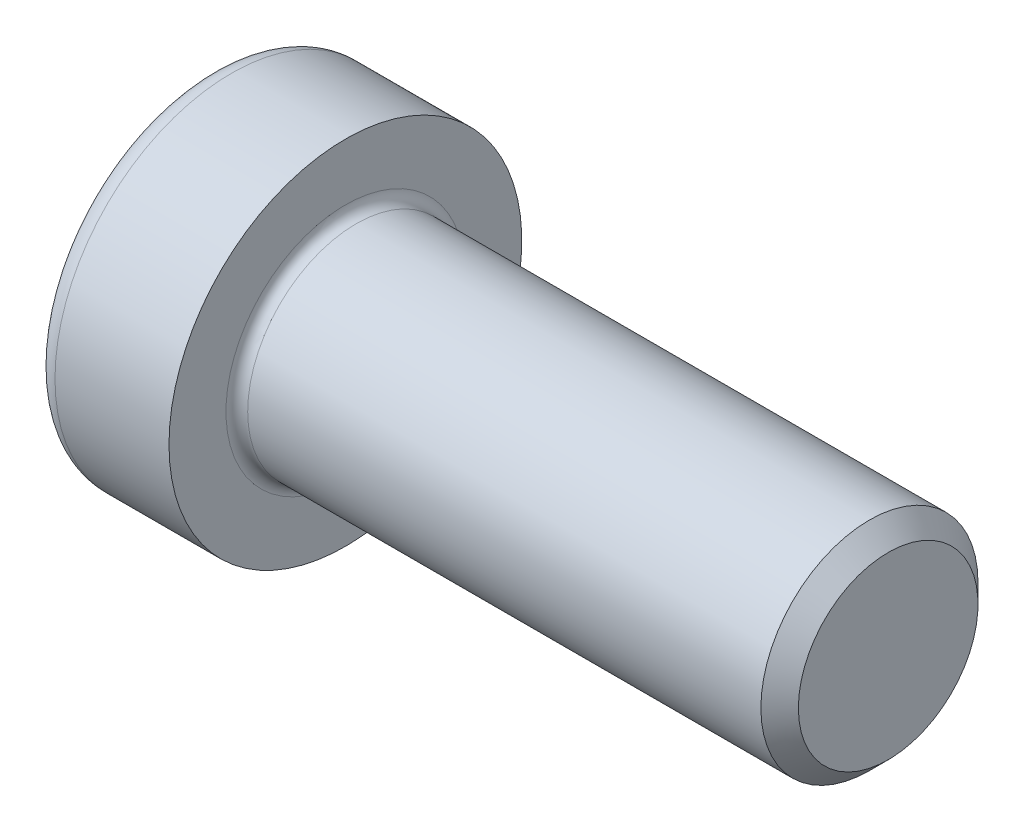
SolidWorks part; units mm, degrees
revolve "Base-Revolve" add sketch "BodySke"
sketch "BodySke" plane through (0, 0, 0) normal (0, 0, 1) x (1, 0, 0)
  line L0 (0, 0) -> (0, 6.5)
  line L1 (0, 6.5) -> (5, 6.5)
  line L2 (5, 6.5) -> (5, 4)
  line L3 (5, 4) -> (24.3095, 4)
  line L4 (25, 3.3095) -> (25, 0)
  line L5 (25, 0) -> (0, 0)
  line L6 (-31.75, 0) -> (127, 0) construction
  line L8 (25, 3.3095) -> (24.3095, 4)
  line L10 (25, -3.3095) -> (24.3095, -4) construction
  line L11 (6.25, 4.525) -> (6.25, -1.825) construction
  line L12 (8.75, 4.525) -> (8.75, -1.825) construction
  line L13 (-35, 4.525) -> (-35, -1.825) construction
  dimension "Head_ht" = 5
  dimension "Length" = 20
  dimension "Body_ch_ang" = 45
  dimension "Diameter" = 8
  dimension "Minor_dia" = 6.619
  dimension "Advance" = 1.25
  dimension "Thread_nom" = 16.25
  dimension "Thread_length" = 60
  dimension "Head_dia" = 13
cosmetic thread "ThreadCosmetic"
fillet "Fillet1" radius 0.4 1 edges at (5, 0, 4)
fillet "Fillet2" radius 0.8 1 edges at (0, 0, 6.5)
material "AISI 316 Нержавеющая сталь, лист (SS)"
ref_plane "Plane1" through (0, 0, 0) normal (0, 0, 1) x (1, 0, 0)
ref_plane "Plane2" through (0, 0, 0) normal (0, 1, 0) x (1, 0, 0)
ref_plane "Plane3" through (0, 0, 0) normal (1, 0, 0) x (0, 0, -1)
other "Configuration Table"
sketch "Sketch2" plane through (0, 0, 0) normal (0, 0, 1) x (1, 0, 0)
  line L0 (0, 2.5) -> (3.8, 2.5)
  line L1 (3.8, 2.5) -> (5.2434, 0)
  line L2 (-31.75, 0) -> (127, 0) construction
  line L3 (5.2434, 0) -> (0, 0)
  line L4 (0, 0) -> (0, 2.5)
  line L6 (0, 0) -> (47.625, 0) construction
  dimension "D1" = 2.5
  dimension "D2" = 60
  dimension "Depth" = 3.8
revolve "Hex-PreBroach" cut sketch "Sketch2" angle 360 about L6
sketch "Sketch3" plane through (0, 0, 0) normal (-1, 0, 0) x (0, 0.5, 0.866)
  line L0 (1.4434, 2.5) -> (-1.4434, 2.5)
  line L1 (-1.4434, 2.5) -> (-2.8868, 0)
  line L2 (1.4434, 2.5) -> (2.8868, 0)
  line L3 (1.4434, -2.5) -> (2.8868, 0)
  line L4 (1.4434, -2.5) -> (-1.4434, -2.5)
  line L5 (-1.4434, -2.5) -> (-2.8868, 0)
  dimension "D1" = 2.5
  dimension "D2" = 2.5
  dimension "Hex_size" = 5
extrude "Hex" cut sketch "Sketch3" against normal blind 3.8
sketch "ThdSchSke" plane through (0, 0, 0) normal (0, 0, 1) x (1, 0, 0)
  line L0 (8.75, -3.3095) -> (8.2665, -4)
  line L1 (8.75, -3.3095) -> (9.2335, -4)
  line L2 (9.2335, -4) -> (9.2335, -5)
  line L3 (-3.175, 0) -> (5.1513, 0) construction
  line L4 (0, 5.7) -> (0, -5.7) construction
  line L5 (9.2335, -5) -> (8.2665, -5)
  line L6 (8.2665, -5) -> (8.2665, -4)
  dimension "Thread_minor" = 6.619
  dimension "Diameter" = 8
  dimension "Start" = 8.75
revolve "ThreadSchematic" [suppressed] cut sketch "ThdSchSke" angle 360 about L3
pattern_linear "ThdSchPat" [suppressed]
equation "\"D2@Sketch3\" = \"Hex_size@Sketch3\" / 2"
equation "\"D1@Sketch3\" = \"Hex_size@Sketch3\" / 2"
equation "\"D1@Sketch2\" = \"Hex_size@Sketch3\" / 2"
equation "\"Thread_minor@ThreadCosmetic\"  =  \"Minor_dia@BodySke\""
equation "\"Depth@Sketch2\" =  \"Key_eng@Hex\""
equation "\"Thread_length@ThreadCosmetic\" = ((sgn( (\"Length@BodySke\" - \"Advance@BodySke\" * 3.0) - \"Thread_nom@BodySke\" )-1)*( (\"Length@BodySke\" - \"Advance@BodySke\" * 3.0) - \"Thread_nom@BodySke\" ))/-2+ \"Thread_nom@BodySke\""
equation "\"Thread_minor@ThdSchSke\" = \"Minor_dia@BodySke\""
equation "\"Diameter@ThdSchSke\" = \"Diameter@BodySke\""
equation "\"Overcut@ThdSchSke\" = \"Diameter@BodySke\" * 1.25"
equation "\"Start@ThdSchSke\" = \"Head_ht@BodySke\" + \"Length@BodySke\" - \"Thread_length@ThreadCosmetic\"  '---Non-countersunk---"
equation "\"Num_threads@ThdSchPat\" = int( \"Thread_length@ThreadCosmetic\" / \"Advance@BodySke\" + 0.999 )  + 1"
equation "\"Advance@ThdSchPat\" = \"Thread_length@ThreadCosmetic\" /  (\"Num_threads@ThdSchPat\" - 1) 'relax it"
equation "\"Num_threads@ThdSchPat\" = \"Num_threads@ThdSchPat\" - sgn( \"Num_threads@ThdSchPat\" - 1) '---chamfered tips only---"
